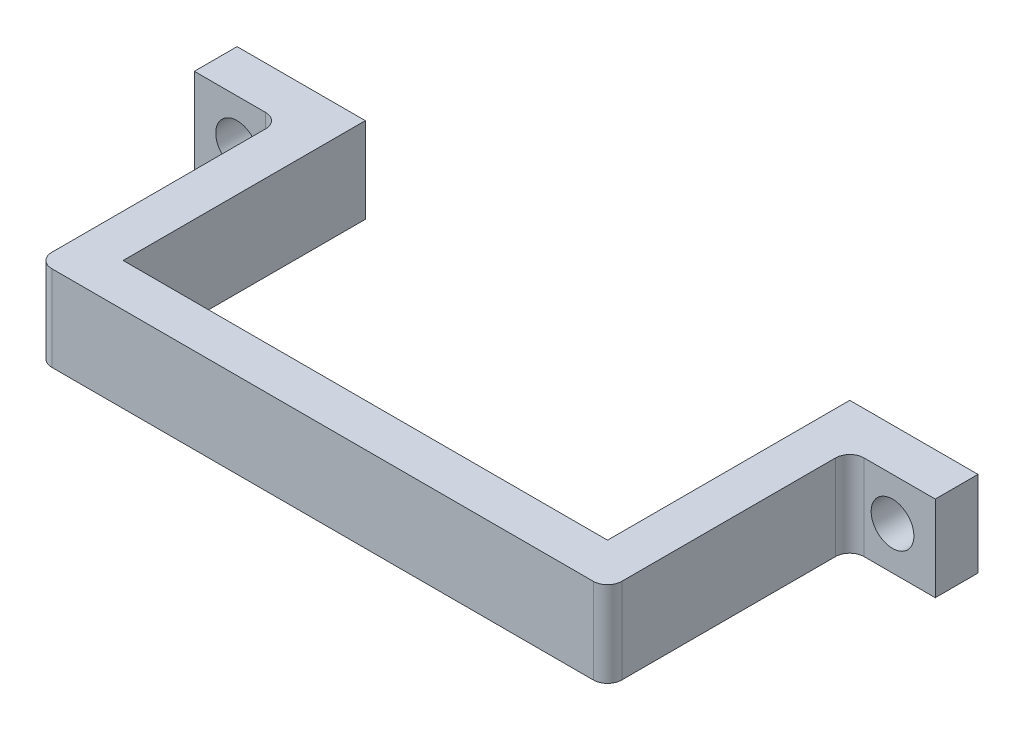
SolidWorks part; units mm, degrees
ref_plane "Front Plane" through (0, 0, 0) normal (0, 0, 1) x (1, 0, 0)
ref_plane "Top Plane" through (0, 0, 0) normal (0, 1, 0) x (1, 0, 0)
ref_plane "Right Plane" through (0, 0, 0) normal (1, 0, 0) x (0, 0, -1)
sketch "Sketch1" plane through (0, 0, 0) normal (0, 1, 0) x (1, 0, 0)
  line L1 (-18.8716, 1.9789) -> (21.1284, 1.9789)
  line L2 (-18.8716, 1.9789) -> (-18.8716, -1.0211)
  line L3 (-18.8716, -1.0211) -> (21.1284, -1.0211)
  line L4 (21.1284, 1.9789) -> (21.1284, -1.0211)
  line L5 (-18.8716, 1.9789) -> (-15.8716, 1.9789)
  line L6 (-18.8716, 1.9789) -> (-18.8716, 18.9789)
  line L7 (-18.8716, 18.9789) -> (-15.8716, 18.9789)
  line L8 (-15.8716, 1.9789) -> (-15.8716, 18.9789)
  line L9 (21.1284, 1.9789) -> (18.1284, 1.9789)
  line L10 (21.1284, 1.9789) -> (21.1284, 18.9789)
  line L11 (21.1284, 18.9789) -> (18.1284, 18.9789)
  line L12 (18.1284, 1.9789) -> (18.1284, 18.9789)
  line L13 (-18.8716, 18.9789) -> (-24.8716, 18.9789)
  line L14 (-18.8716, 18.9789) -> (-18.8716, 15.9789)
  line L15 (-18.8716, 15.9789) -> (-24.8716, 15.9789)
  line L16 (-24.8716, 18.9789) -> (-24.8716, 15.9789)
  line L17 (21.1284, 18.9789) -> (27.1284, 18.9789)
  line L18 (21.1284, 18.9789) -> (21.1284, 15.9789)
  line L19 (21.1284, 15.9789) -> (27.1284, 15.9789)
  line L20 (27.1284, 18.9789) -> (27.1284, 15.9789)
  dimension "D1" = 40
  dimension "D2" = 3
  dimension "D3" = 17
  dimension "D4" = 3
  dimension "D5" = 3
  dimension "D6" = 17
  dimension "D7" = 6
  dimension "D8" = 3
  dimension "D9" = 6
  dimension "D10" = 3
extrude "Boss-Extrude1" add sketch "Sketch1" along normal blind 6 contours L13 L16 L15 L6 | L1 L8 L7 L6 | L4 L1 L2 L3 | L12 L1 L10 L11 | L20 L17 L10 L19
sketch "Sketch2" plane through (0, 0, -15.9789) normal (0, 0, 1) x (1, 0, 0)
  line L0 (27.1284, 6) -> (27.1284, 0) construction
  line L1 (21.1284, 6) -> (27.1284, 6) construction
  line L2 (-24.8716, 6) -> (-24.8716, 0) construction
  line L3 (-18.8716, 0) -> (-24.8716, 0) construction
  circle A0 centre (-21.8716, 3) radius 1.5
  circle A1 centre (24.1284, 3) radius 1.5
  point P8 (38.7724, 7.3706)
  dimension "D1" = 3
  dimension "D2" = 3
  dimension "D3" = 3
  dimension "D4" = 3
  dimension "D5" = 3
  dimension "D6" = 3
extrude "Cut-Extrude1" cut sketch "Sketch2" against normal blind 6
fillet "Fillet1" radius 1 1 edges at (-18.8716, 3, -15.9789)
fillet "Fillet2" radius 1 1 edges at (21.1284, 3, -15.9789)
fillet "Fillet3" radius 1 1 edges at (21.1284, 3, 1.0211)
fillet "Fillet4" radius 1 1 edges at (-18.8716, 3, 1.0211)
